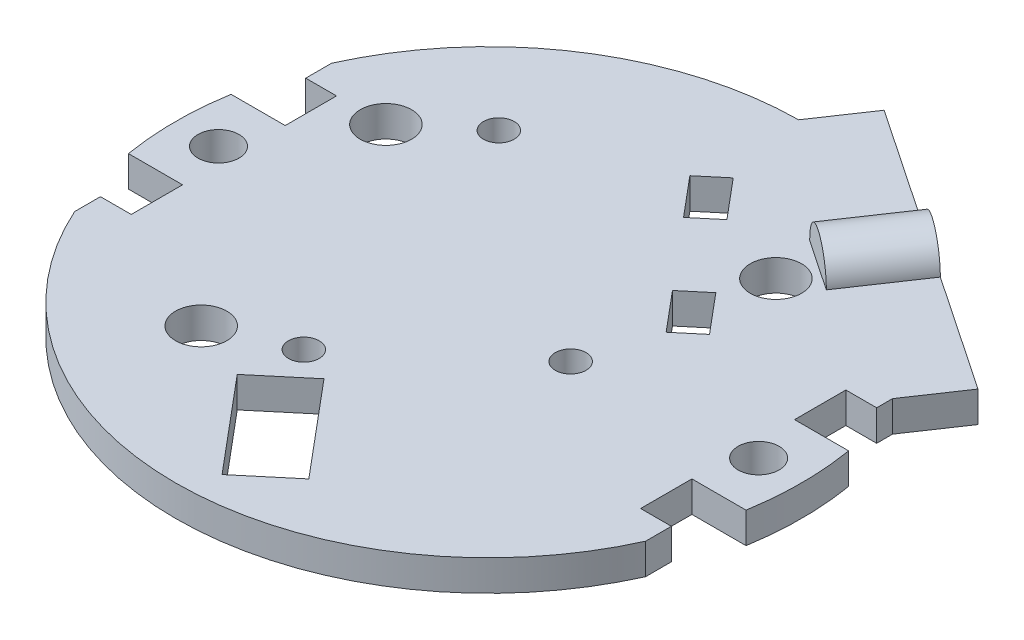
SolidWorks part; units mm, degrees
ref_plane "Alzado" through (0, 0, 0) normal (0, 0, 1) x (1, 0, 0)
ref_plane "Planta" through (0, 0, 0) normal (0, 1, 0) x (1, 0, 0)
ref_plane "Vista lateral" through (0, 0, 0) normal (1, 0, 0) x (0, 0, -1)
sketch "Croquis1" plane through (0, 0, 0) normal (0, 1, 0) x (1, 0, 0)
  circle A0 centre (0, 0) radius 30.5
extrude "Saliente-Extruir1" add sketch "Croquis1" along normal blind 3
sketch "Croquis5" plane through (0, 3, 0) normal (0, 1, 0) x (1, 0, 0)
  line L0 (0, 0) -> (0, 10)
  line L1 (28.8141, -5) -> (30.0874, -5)
  line L2 (28.8141, 5) -> (30.0874, 5)
  line L3 (-24.8141, 10) -> (-28.8141, 10)
  line L4 (24.8141, -5) -> (24.8141, -10)
  line L5 (-24.8141, -10) -> (-28.8141, -10)
  line L6 (24.8141, -5) -> (28.8141, -5)
  line L7 (24.8141, 5) -> (24.8141, 10)
  line L8 (-24.8141, 5) -> (-28.8141, 5)
  line L9 (-24.8141, 5) -> (-24.8141, 10)
  line L10 (-24.8141, -5) -> (-28.8141, -5)
  line L11 (-24.8141, -5) -> (-24.8141, -10)
  line L12 (24.8141, 5) -> (28.8141, 5)
  line L13 (24.8141, -10) -> (28.8141, -10)
  line L14 (24.8141, 10) -> (28.8141, 10)
  line L15 (-28.8141, 5) -> (-30.0874, 5)
  line L16 (-28.8141, -5) -> (-30.0874, -5)
  circle A1 centre (0, 0) radius 30.5 construction
  arc A2 (-28.8141, 10) -> (-30.0874, 5) centre (0, 0) ccw
  arc A3 (28.8141, 10) -> (28.8141, -10) centre (0, 0) cw
  arc A4 (-30.0874, -5) -> (-28.8141, -10) centre (0, 0) ccw
  arc A5 (30.0874, -5) -> (28.8141, -10) centre (0, 0) cw
  arc A6 (28.8141, 10) -> (30.0874, 5) centre (0, 0) cw
extrude "Cortar-Extruir3" cut sketch "Croquis5" against normal blind 4
sketch "Croquis7" plane through (0, 3, 0) normal (0, 1, 0) x (1, 0, 0)
  line L0 (-8.1011, 29.1011) -> (9.5756, 8.0348)
  line L1 (9.5756, 8.0348) -> (27.2522, -13.0314)
  line L2 (-8.1011, 29.1011) -> (-27.2522, 13.0314)
  line L3 (27.2522, -13.0314) -> (8.1011, -29.1011)
  line L4 (8.1011, -29.1011) -> (-27.2522, 13.0314)
  line L5 (1.4284, 22.4114) -> (-0.8697, 20.4831)
  line L6 (1.4284, 22.4114) -> (4.6423, 18.5812)
  line L7 (4.6423, 18.5812) -> (2.3442, 16.6528)
  line L8 (2.3442, 16.6528) -> (-0.8697, 20.4831)
  line L9 (7.9686, 9.95) -> (11.1825, 6.1197)
  line L10 (8.1011, -29.1011) -> (5.53, -26.0369)
  line L11 (10.2667, 11.8783) -> (13.4807, 8.0481)
  line L12 (13.4807, 8.0481) -> (11.1825, 6.1197)
  line L13 (10.2667, 11.8783) -> (7.9686, 9.95)
  line L14 (5.53, -26.0369) -> (10.8923, -21.5374)
  line L15 (10.8923, -21.5374) -> (-19.3188, 14.4667)
  line L17 (-24.6811, 9.9672) -> (-19.3188, 14.4667)
  point P7 (-9.5756, -8.0348)
extrude "Cortar-Extruir5" cut sketch "Croquis7" against normal blind 4 contours L7 L6 L5 L0 | L11 L13 L0 L1 L12
sketch "Croquis8" plane through (0, 3, 0) normal (0, 1, 0) x (1, 0, 0)
  line L0 (-11.3137, 11.3137) -> (0, 0)
  line L2 (0, 0) -> (12, 0)
  line L3 (0, 0) -> (-11.3137, 11.3137)
  line L4 (12, 0) -> (12, 16)
  line L5 (0, 0) -> (-12, 0)
  line L6 (-12, 0) -> (-12, -16)
  line L10 (1.5586, -27.5246) -> (6.1549, -23.6679)
  line L11 (6.1549, -23.6679) -> (-1.5586, -14.4754)
  line L13 (-6.1549, -18.3321) -> (-1.5586, -14.4754)
  line L14 (1.5586, -27.5246) -> (-6.1549, -18.3321)
  circle A0 centre (0, 0) radius 30
  circle A1 centre (9, -1) radius 1.5
  circle A2 centre (-5, -13) radius 1.5
  circle A3 centre (-12, -16) radius 2.5
  circle A4 centre (-14, 15) radius 1.5
  circle A5 centre (12, 16) radius 2.5
  point P20 (-3.8567, -16.4037)
extrude "Cortar-Extruir6" cut sketch "Croquis8" against normal blind 10
sketch "Croquis10" plane through (0, 3, 0) normal (0, 1, 0) x (1, 0, 0)
  line L0 (-24.8141, 10) -> (-27.8141, 10)
  line L2 (-24.8141, 10) -> (-28.8141, 10) construction
  line L4 (-27.8141, 10) -> (-27.8141, 12.5151)
  line L6 (-27.8141, 10) -> (-28.8141, 10)
  line L14 (-27.8141, -10) -> (-28.8141, -10)
  line L15 (-27.8141, -10) -> (-27.8141, -12.5151)
  line L16 (27.8141, -10) -> (27.8141, -12.5151)
  line L17 (27.8141, -10) -> (28.8141, -10)
  line L21 (27.8141, 10) -> (28.8141, 10)
  line L22 (27.8141, 10) -> (27.8141, 12.5151)
  line L23 (24.8141, 10) -> (27.8141, 10)
  circle A0 centre (-26.3141, 0) radius 2
  circle A1 centre (26.3141, 0) radius 2
  arc A2 (28.8141, 10) -> (-28.8141, 10) centre (0, 0) ccw construction
  arc A5 (-27.8141, 12.5151) -> (-28.8141, 10) centre (0, 0) ccw
  arc A7 (-27.8141, -12.5151) -> (-28.8141, -10) centre (0, 0) cw
  arc A8 (27.8141, -12.5151) -> (28.8141, -10) centre (0, 0) ccw
  arc A10 (27.8141, 12.5151) -> (28.8141, 10) centre (0, 0) cw
  line M13 (24.8141, 10) -> (28.8141, 10)
  arc M14 (28.8141, 10) -> (-28.8141, 10) centre (0, 0) ccw
  line M15 (-28.8141, 10) -> (-24.8141, 10)
  line M21 (-24.8141, -10) -> (-28.8141, -10)
  arc M22 (-28.8141, -10) -> (28.8141, -10) centre (0, 0) ccw
  line M23 (28.8141, -10) -> (24.8141, -10)
extrude "Cortar-Extruir8" cut sketch "Croquis10" against normal blind 3 contours L15 M21 M22 | L4 M15 M14 | L16 M23 M22 | L22 M13 M14 | A0 | A1
sketch "Croquis11" plane through (0, 3, 0) normal (0, 1, 0) x (1, 0, 0)
  line L0 (0, 0) -> (-20, 0)
  line L1 (-20, 0) -> (-20, 10)
  line L2 (0, 0) -> (0, 4.5949)
  line L3 (29.8013, 10.2046) -> (-1.7022, 31.454)
  circle A0 centre (-20, 10) radius 2.5
  circle A5 centre (0, 0) radius 31.5
extrude "Cortar-Extruir9" cut sketch "Croquis11" against normal blind 3
sketch "Croquis13" plane through (14.0495, 0, -20.8293) normal (0.5592, 0, -0.829) x (-0.829, 0, -0.5592)
  line L1 (-16.603, 0) -> (17.2916, 0)
  line L2 (-16.603, 0) -> (-16.603, 3)
  line L3 (-16.603, 3) -> (17.2916, 3)
  line L4 (17.2916, 0) -> (17.2916, 3)
extrude "Saliente-Extruir2" add sketch "Croquis13" along normal blind 6
sketch "Croquis14" plane through (17.4047, 0, -25.8035) normal (0.5592, 0, -0.829) x (-0.829, 0, -0.5592)
  circle A0 centre (0.0043, 3) radius 3
extrude "Saliente-Extruir3" add sketch "Croquis14" against normal blind 8
sketch "Croquis17" plane through (17.4047, 0, -25.8035) normal (0.5592, 0, -0.829) x (-0.829, 0, -0.5592)
  circle A0 centre (0.0043, 3) radius 1.5
extrude "Cortar-Extruir10" cut sketch "Croquis17" against normal blind 7
